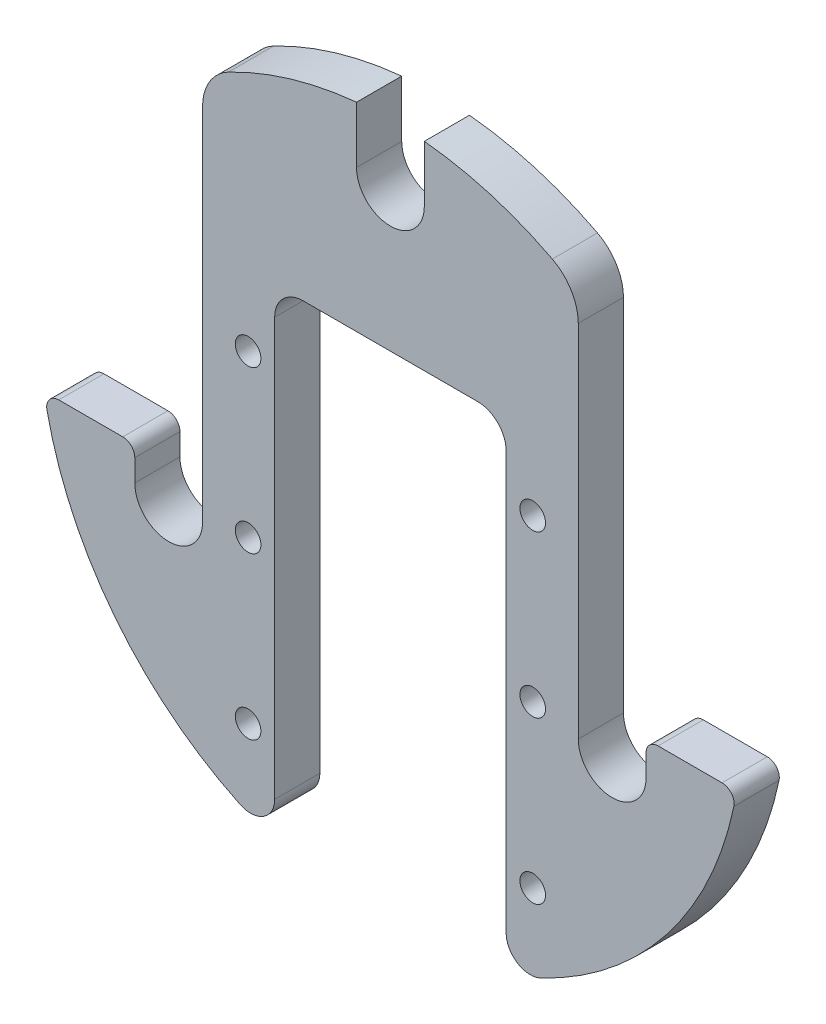
SolidWorks part; units mm, degrees
ref_plane "Front Plane" through (0, 0, 0) normal (0, 0, 1) x (1, 0, 0)
ref_plane "Top Plane" through (0, 0, 0) normal (0, 1, 0) x (1, 0, 0)
ref_plane "Right Plane" through (0, 0, 0) normal (1, 0, 0) x (0, 0, -1)
sketch "Sketch2" plane through (0, 0, 0) normal (0, 0, 1) x (1, 0, 0)
  line L0 (-9.2, 12) -> (9.2, 12)
  line L1 (-12.2, -30) -> (-12.2, 9) construction
  line L2 (-23.3719, 13.4938) -> (0, -38.6) construction
  line L3 (0, -38.6) -> (23.3719, 13.4938) construction
  line L4 (23.3719, 13.4938) -> (12.2, 13.4938) construction
  line L5 (0, 13.4938) -> (0, -38.6) construction
  line L7 (23.3719, 13.4938) -> (-11.6859, -12.5531) construction
  line L8 (12.2, 9) -> (12.2, -30) construction
  line L9 (-12.2, -30) -> (-12.2, 9)
  line L11 (12.2, 9) -> (12.2, -30)
  line L12 (-12.2, -30) -> (-12.2, -35.006)
  line L13 (12.2, -30) -> (12.2, -35.006)
  line L15 (-12.2, 13.4938) -> (-23.3719, 13.4938) construction
  arc A0 (-12.2, 31.0473) -> (-15.8268, -37.3018) centre (0, -3.8708) ccw
  circle A1 centre (-15, -12.5) radius 1.35 construction
  arc A2 (-9.2, 12) -> (-12.2, 9) centre (-9.2, 9) ccw construction
  circle A4 centre (-15, 4.5) radius 1.35 construction
  circle A5 centre (-15, -29.5) radius 1.35 construction
  circle A8 centre (15, -29.5) radius 1.35 construction
  circle A9 centre (15, -12.5) radius 1.35 construction
  circle A10 centre (15, 4.5) radius 1.35 construction
  circle A11 centre (-15, -12.5) radius 1.35
  arc A13 (12.2, 9) -> (9.2, 12) centre (9.2, 9) ccw construction
  arc A14 (-12.2, 31.0473) -> (12.2, 31.0473) centre (0, -3.8708) cw
  circle A17 centre (-15, 4.5) radius 1.35
  circle A18 centre (-15, -29.5) radius 1.35
  circle A21 centre (15, -29.5) radius 1.35
  circle A22 centre (15, -12.5) radius 1.35
  circle A23 centre (15, 4.5) radius 1.35
  arc A24 (-9.2, 12) -> (-12.2, 9) centre (-9.2, 9) ccw
  arc A25 (12.2, 9) -> (9.2, 12) centre (9.2, 9) ccw
  arc A26 (15.8268, -37.3018) -> (12.2, 31.0473) centre (0, -3.8708) ccw
  arc A27 (15.8268, -37.3018) -> (12.2, -35.006) centre (14.74, -35.006) cw
  arc A28 (-12.2, -35.006) -> (-15.8268, -37.3018) centre (-14.74, -35.006) cw
  point P30 (0, -3.8708)
  point P51 (12.2, -38.789)
  dimension "D1" = 2.54
extrude "Boss-Extrude1" add sketch "Sketch2" along normal blind 4.7625
hole_wizard "1/4 Clearance Hole1" positions "Sketch4" profile "Sketch3" hole size "1/4" standard "ANSI Inch"
sketch "Sketch4" plane through (0, 0, 4.7625) normal (0, 0, 1) x (1, 0, 0)
  point P0 (-23.3719, -13.4937)
  point P3 (23.3719, -13.4938)
  point P6 (0, 26.9875)
sketch "Sketch3" plane through (-23.3719, -13.4937, 4.7625) normal (1, 0, 0) x (0, -1, 0)
  line L0 (0, 0) -> (0, 8.4958)
  line L1 (0, 8.4958) -> (3.5712, 6.35)
  line L2 (3.5712, 6.35) -> (3.5712, 0)
  line L5 (3.5712, 0) -> (0, 0)
  line L10 (0, 8.4958) -> (-3.5712, 6.35) construction
  line L11 (0, -6.35) -> (0, 107.95) construction
  dimension "Hole Dia." = 7.1425
  dimension "Hole Depth" = 6.35
  dimension "Drill Angle" = 118
sketch "Sketch5" plane through (0, 0, 4.7625) normal (0, 0, 1) x (1, 0, 0)
  line L0 (19.8006, -13.4937) -> (-19.8006, -13.4937) construction
  line L1 (3.5712, 26.9875) -> (3.5712, 32.9444)
  line L2 (0, -13.4937) -> (0, 12) construction
  line L3 (28.2131, -9.9225) -> (34.9596, -9.9225)
  line L4 (26.9431, -13.4938) -> (26.9431, -11.1925)
  line L5 (19.8006, -13.4938) -> (19.8006, 24.4387)
  line L6 (-9.2, 12) -> (9.2, 12) construction
  line L7 (-28.2131, -9.9225) -> (-34.9596, -9.9225)
  line L8 (-26.9431, -13.4938) -> (-26.9431, -11.1925)
  line L9 (-19.8006, -13.4938) -> (-19.8006, 24.4387)
  line L10 (-3.5712, 26.9875) -> (-3.5712, 32.9444)
  circle A0 centre (23.3719, -13.4938) radius 3.5712 construction
  circle A1 centre (-23.3719, -13.4937) radius 3.5712 construction
  circle A2 centre (0, 26.9875) radius 3.5712 construction
  arc A3 (15.8268, -37.3018) -> (-15.8268, -37.3018) centre (0, -3.8708) ccw construction
  arc A4 (36.4896, -9.9225) -> (19.8006, 27.371) centre (0, -3.8708) ccw
  arc A5 (-3.5712, 26.9875) -> (3.5712, 26.9875) centre (0, 26.9875) ccw
  arc A6 (-26.9431, -13.4938) -> (-19.8006, -13.4938) centre (-23.3719, -13.4937) ccw
  arc A7 (19.8006, -13.4938) -> (26.9431, -13.4938) centre (23.3719, -13.4938) ccw
  arc A8 (19.8006, 27.371) -> (17.0643, 28.9457) centre (0, -3.8708) ccw
  arc A9 (-19.8006, 27.371) -> (-36.4896, -9.9225) centre (0, -3.8708) ccw
  arc A10 (26.9431, -11.1925) -> (28.2131, -9.9225) centre (28.2131, -11.1925) cw
  arc A11 (-28.2131, -9.9225) -> (-26.9431, -11.1925) centre (-28.2131, -11.1925) cw
  arc A12 (-19.8006, 27.371) -> (-17.0643, 28.9457) centre (0, -3.8708) cw
  arc A13 (-17.0643, 28.9457) -> (-19.8006, 24.4387) centre (-14.7206, 24.4387) ccw
  arc A14 (17.0643, 28.9457) -> (19.8006, 24.4387) centre (14.7206, 24.4387) cw
  arc A15 (-36.4896, -9.9225) -> (-36.2026, -11.4528) centre (0, -3.8708) ccw
  arc A16 (-34.9596, -9.9225) -> (-36.2026, -11.4528) centre (-34.9596, -11.1925) ccw
  arc A17 (36.4896, -9.9225) -> (36.2026, -11.4528) centre (0, -3.8708) cw
  arc A18 (34.9596, -9.9225) -> (36.2026, -11.4528) centre (34.9596, -11.1925) cw
  point P31 (26.9431, -9.9225)
  point P34 (-26.9431, -9.9225)
  circle M1 centre (-23.3719, -13.4937) radius 3.5712
  circle M2 centre (23.3719, -13.4938) radius 3.5712
  circle M3 centre (0, 26.9875) radius 3.5712
  arc M13 (15.8268, -37.3018) -> (-15.8268, -37.3018) centre (0, -3.8708) ccw
  dimension "D1" = 1.27
  dimension "D2" = 5.08
  dimension "D3" = 5.08
  dimension "D4" = 1.27
  dimension "D5" = 1.27
extrude "Cut-Extrude1" cut sketch "Sketch5" against normal up to surface (4.7625 mm away) contours L3 A18 A14 L5 L4 A10 M13 M2 | L10 L1 M3 M13 | A16 L7 A11 L8 L9 A13 M1 M13 up to face at (-26.9431, -13.4937, 0)
